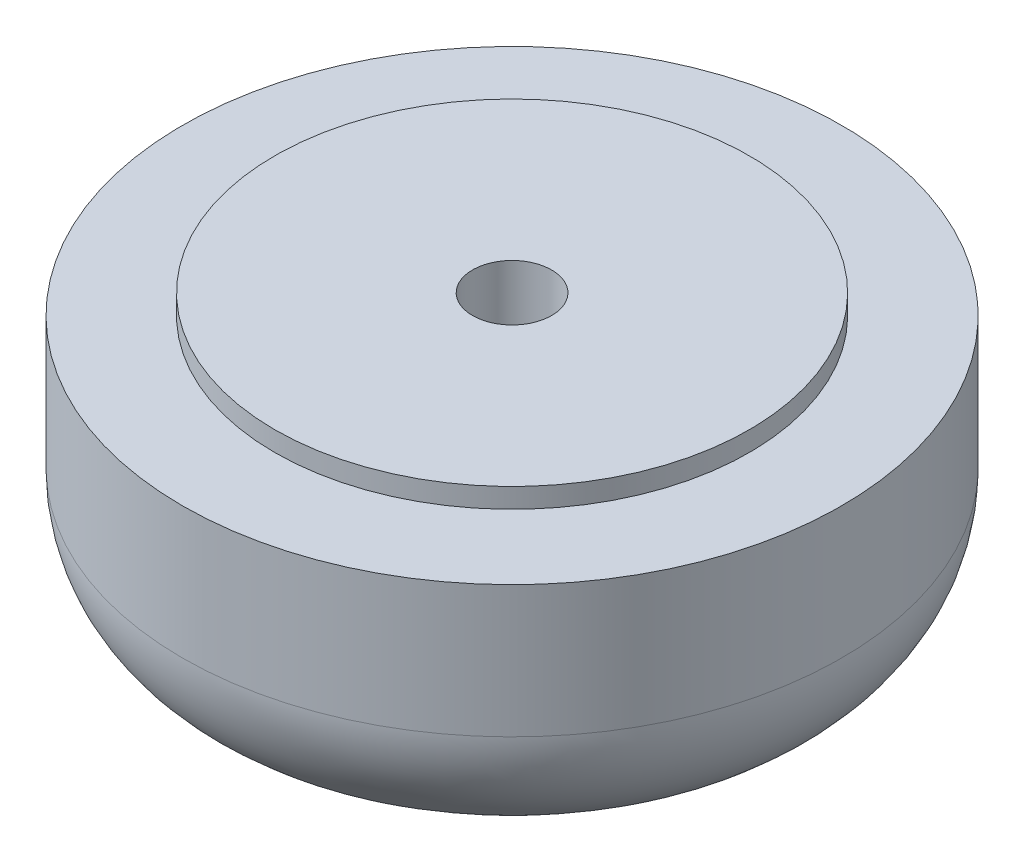
SolidWorks part; units mm, degrees
ref_plane "前视基准面" through (0, 0, 0) normal (0, 0, 1) x (1, 0, 0)
ref_plane "上视基准面" through (0, 0, 0) normal (0, 1, 0) x (1, 0, 0)
ref_plane "右视基准面" through (0, 0, 0) normal (1, 0, 0) x (0, 0, -1)
other "Configuration Table"
sketch "草图1" plane through (0, 0, 0) normal (0, 1, 0) x (1, 0, 0)
  circle A0 centre (0, 0) radius 5
  dimension "D1" = 10
extrude "凸台-拉伸1" add sketch "草图1" along normal blind 4
sketch "草图2" plane through (0, 4, 0) normal (0, 1, 0) x (1, 0, 0)
  circle A0 centre (0, 0) radius 3.6
  dimension "D1" = 7.2
extrude "凸台-拉伸2" add sketch "草图2" along normal blind 0.3
fillet "圆角1" radius 2 1 edges at (0, 0, 5)
sketch "草图3" plane through (0, 4.3, 0) normal (0, 1, 0) x (1, 0, 0)
  circle A0 centre (0, 0) radius 0.6
  dimension "D1" = 1.2
extrude "切除-拉伸1" cut sketch "草图3" against normal through all
